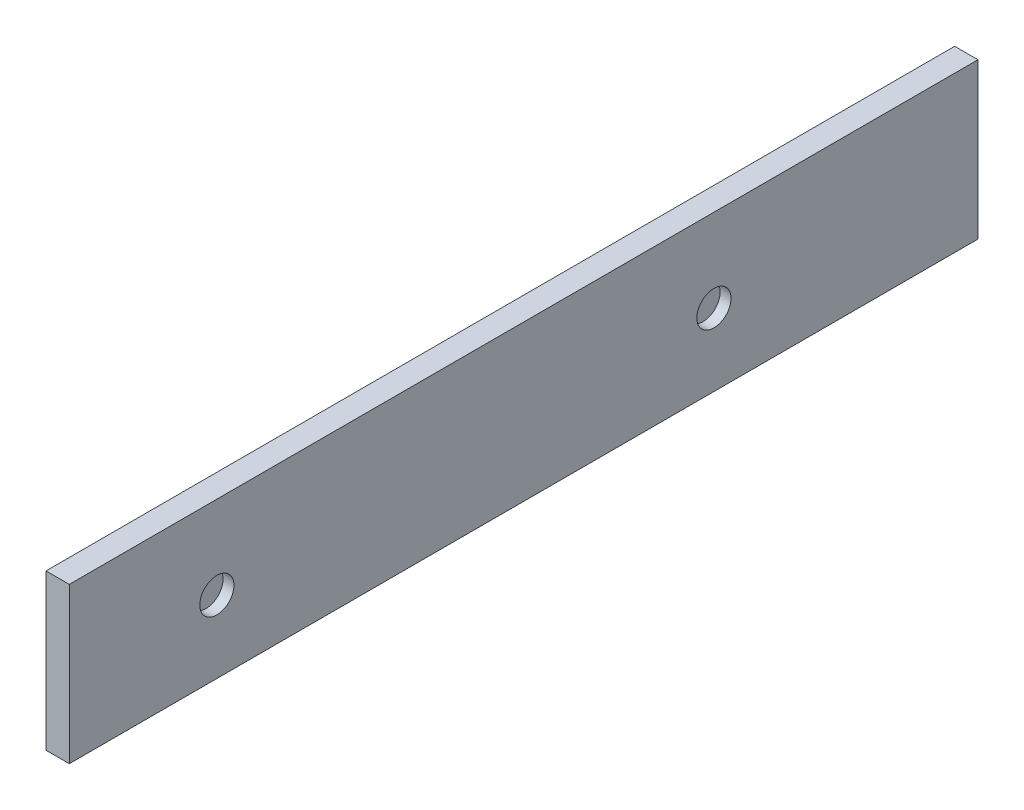
SolidWorks part; units mm, degrees
ref_plane "Alzado" through (0, 0, 0) normal (0, 0, 1) x (1, 0, 0)
ref_plane "Planta" through (0, 0, 0) normal (0, 1, 0) x (1, 0, 0)
ref_plane "Vista lateral" through (0, 0, 0) normal (1, 0, 0) x (0, 0, -1)
sketch "Croquis1" plane through (0, 0, 0) normal (1, 0, 0) x (0, 0, -1)
  line L1 (0, 0) -> (585, 0)
  line L2 (0, 0) -> (0, 100)
  line L3 (0, 100) -> (585, 100)
  line L4 (585, 0) -> (585, 100)
  dimension "D1" = 585
  dimension "D2" = 100
extrude "Saliente-Extruir1" add sketch "Croquis1" along normal blind 15
sketch "Croquis2" plane through (15, 0, 0) normal (1, 0, 0) x (0, 0, -1)
  line L0 (0, 0) -> (585, 0) construction
  line L4 (585, 0) -> (585, 100) construction
  line L5 (255, 100) -> (255, 0) construction
  line L6 (585, 100) -> (0, 100) construction
  circle A0 centre (95, 46.5) radius 11
  circle A1 centre (415, 46.5) radius 11
  dimension "D1" = 22
  dimension "D2" = 46.5
  dimension "D3" = 160
  dimension "D4" = 330
  dimension "D5" = 160
extrude "Cortar-Extruir1" cut sketch "Croquis2" against normal blind 7
